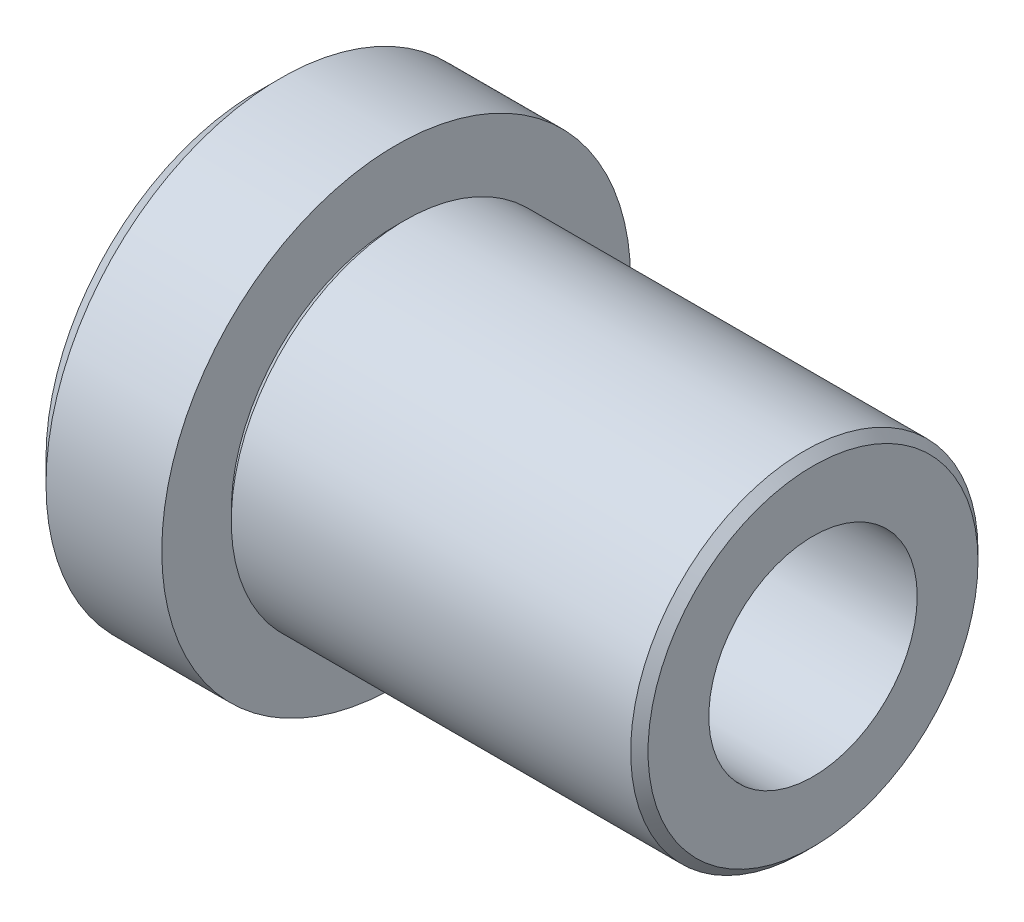
SolidWorks part; units mm, degrees
ref_plane "Front Plane" through (0, 0, 0) normal (0, 0, 1) x (1, 0, 0)
ref_plane "Top Plane" through (0, 0, 0) normal (0, 1, 0) x (1, 0, 0)
ref_plane "Right Plane" through (0, 0, 0) normal (1, 0, 0) x (0, 0, -1)
sketch "Sketch1" plane through (0, 0, 0) normal (1, 0, 0) x (0, 0, -1)
  circle A0 centre (0, 0) radius 2.3812 construction
  circle A1 centre (0, 0) radius 5.3578 construction
  point P4 (5.3578, 0)
  point P5 (-5.3578, 0)
  point P6 (2.3812, 0)
  point P7 (-2.3812, 0)
  dimension "Head OD" = 10.7156
  dimension "ID" = 4.7625
sketch "Sketch2" plane through (0, 0, 0) normal (0, 0, 1) x (1, 0, 0)
  line L0 (6.35, 2.3812) -> (-5.8208, 2.3812) construction
  line L1 (6.35, 2.3812) -> (6.35, 3.7703) construction
  line L2 (-5.8208, 5.3578) -> (-6.35, 4.8286) construction
  line L3 (6.1516, 3.9687) -> (-2.9766, 3.9687) construction
  line L4 (-2.9766, 3.9687) -> (-3.175, 3.7703) construction
  line L5 (-3.175, 3.7703) -> (-3.175, 5.3578) construction
  line L6 (-3.175, 5.3578) -> (-5.8208, 5.3578) construction
  line L7 (-6.35, 2.9104) -> (-5.8208, 2.3812) construction
  line L8 (-6.35, 4.8286) -> (-6.35, 2.9104) construction
  line L9 (6.35, 3.7703) -> (6.1516, 3.9687) construction
  line L10 (6.35, 0) -> (-6.35, 0) construction
  line L11 (-6.35, 5.3578) -> (-6.35, -5.3578) construction
  point P3 (6.35, 3.9687)
  point P8 (-6.35, 5.3578)
  point P11 (-6.35, 2.3812)
  point P16 (-6.35, -5.3578)
  point P17 (-3.175, -5.3578)
  point P29 (-6.35, 0)
  dimension "Length" = 9.525
  dimension "D2" = 0.5292
  dimension "D3" = 45
  dimension "D4" = 0.5292
  dimension "D5" = 45
  dimension "D7" = 45
  dimension "OD" = 7.9375
  dimension "D9" = 4.7625
  dimension "D8" = 10.7156
  dimension "D1" = 1.5875
  dimension "D6" = 0.1984
  dimension "Head Thickness" = 3.175
sketch "Sketch3" plane through (0, 0, 0) normal (0, 0, 1) x (1, 0, 0)
  line L0 (6.35, 2.3812) -> (6.35, 3.7703)
  line L1 (6.35, 3.7703) -> (6.1516, 3.9687)
  line L2 (6.1516, 3.9687) -> (-2.9766, 3.9687)
  line L3 (-2.9766, 3.9687) -> (-3.175, 3.7703)
  line L4 (-3.175, 3.7703) -> (-3.175, 5.3578)
  line L5 (-3.175, 5.3578) -> (-5.8208, 5.3578)
  line L6 (-5.8208, 5.3578) -> (-6.35, 4.8286)
  line L7 (-6.35, 4.8286) -> (-6.35, 2.9104)
  line L8 (-6.35, 2.9104) -> (-5.8208, 2.3812)
  line L9 (-5.8208, 2.3812) -> (6.35, 2.3812)
revolve "Revolve1" add sketch "Sketch3" angle 360 about L10
equation "\"D2@Sketch2\" = \"Head Thickness@Sketch2\" / 6"
equation "\"D4@Sketch2\" = \"D2@Sketch2\""
equation "\"D9@Sketch2\" = \"ID@Sketch1\""
equation "\"D8@Sketch2\" = \"Head OD@Sketch1\""
equation "\"D6@Sketch2\"=\"OD@Sketch2\"*.025"
